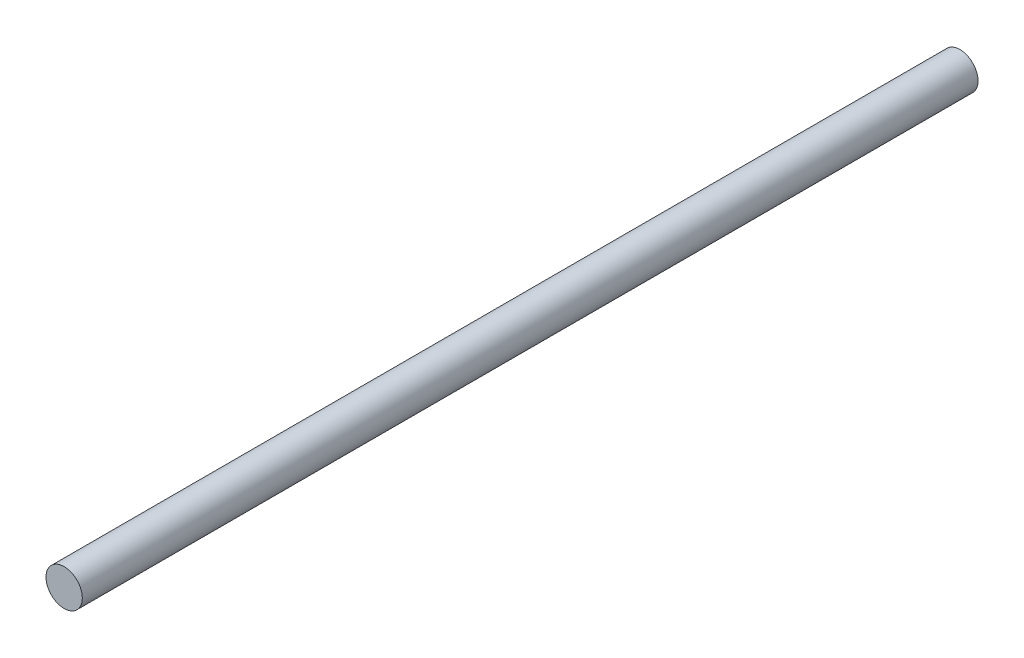
SolidWorks part; units mm, degrees
material "1.7036 (28CrS4)"
ref_plane "정면" through (0, 0, 0) normal (0, 0, 1) x (1, 0, 0)
ref_plane "윗면" through (0, 0, 0) normal (0, 1, 0) x (1, 0, 0)
ref_plane "우측면" through (0, 0, 0) normal (1, 0, 0) x (0, 0, -1)
sketch "스케치1" plane through (0, 0, 0) normal (0, 0, 1) x (1, 0, 0)
  circle A0 centre (0, 0) radius 5
  dimension "D1" = 10
extrude "보스-돌출1" add sketch "스케치1" along normal blind 218.44
sketch "스케치2" plane through (0, 0, 218.44) normal (0, 0, 1) x (1, 0, 0)
  text T0 "TEST\r\n"
sketch "스케치3" plane through (0, 0, 0) normal (0, 0, -1) x (-1, 0, 0)
  circle A0 centre (0, 0) radius 5
  dimension "D1" = 10
extrude "보스-돌출2" add sketch "스케치3" along normal blind 28.36
equation "\"`\"=4"
